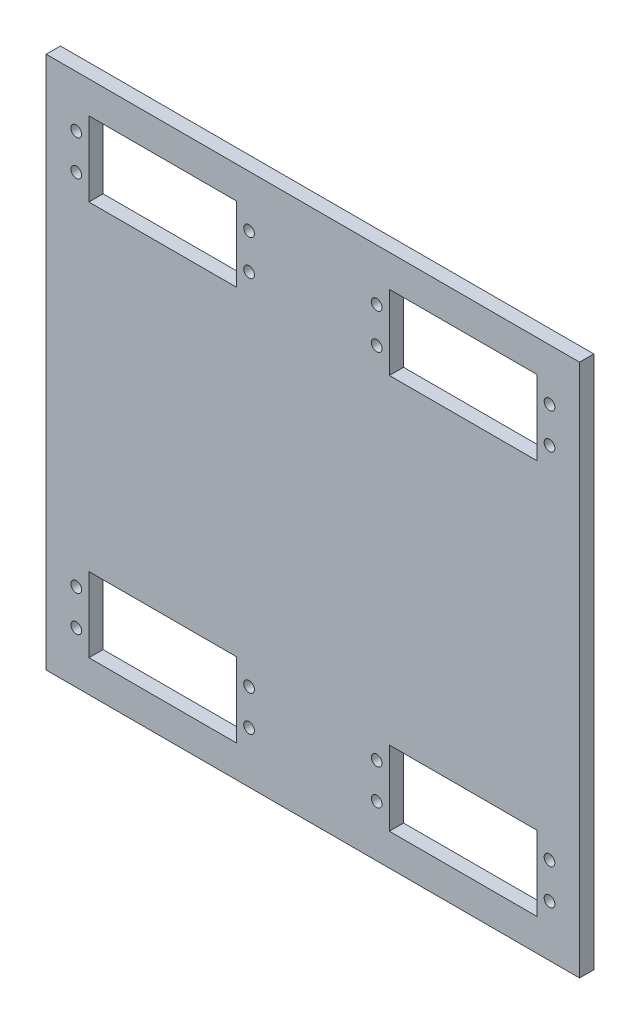
SolidWorks part; units mm, degrees
ref_plane "Plano frontal" through (0, 0, 0) normal (0, 0, 1) x (1, 0, 0)
ref_plane "Plano superior" through (0, 0, 0) normal (0, 1, 0) x (1, 0, 0)
ref_plane "Plano direito" through (0, 0, 0) normal (1, 0, 0) x (0, 0, -1)
sketch "Esboço1" plane through (0, 0, 0) normal (0, 0, 1) x (1, 0, 0)
  line L0 (66.55, 60.5) -> (66.55, 50.5) construction
  line L1 (-75, 75) -> (75, 75)
  line L2 (-75, 75) -> (-75, -75)
  line L3 (-75, -75) -> (75, -75)
  line L4 (75, 75) -> (75, -75)
  line L5 (-75, 75) -> (75, -75) construction
  line L6 (-75, -75) -> (75, 75) construction
  line L7 (-63, 66) -> (-21.5, 66)
  line L8 (-63, 66) -> (-63, 45)
  line L9 (-63, 45) -> (-21.5, 45)
  line L10 (-21.5, 66) -> (-21.5, 45)
  line L11 (69.6, 45) -> (63, 45) construction
  line L12 (69.6, 66) -> (69.6, 45) construction
  line L13 (63, 66) -> (69.6, 66) construction
  line L14 (14.9, 45) -> (21.5, 45) construction
  line L15 (14.9, 66) -> (14.9, 45) construction
  line L16 (21.5, 66) -> (14.9, 66) construction
  line L17 (21.5, 66) -> (21.5, 45)
  line L18 (63, 45) -> (21.5, 45)
  line L19 (63, 66) -> (63, 45)
  line L20 (63, 66) -> (21.5, 66)
  line L21 (-66.55, -60.5) -> (-66.55, -50.5) construction
  line L22 (-69.6, -45) -> (-63, -45) construction
  line L23 (-69.6, -66) -> (-69.6, -45) construction
  line L24 (-63, -66) -> (-69.6, -66) construction
  line L25 (-14.9, -45) -> (-21.5, -45) construction
  line L26 (-14.9, -66) -> (-14.9, -45) construction
  line L27 (-21.5, -66) -> (-14.9, -66) construction
  line L28 (-42.25, 66) -> (-42.25, 75) construction
  line L29 (-63, 55.5) -> (-75, 55.5) construction
  line L30 (-21.5, 66) -> (-14.9, 66) construction
  line L31 (-14.9, 66) -> (-14.9, 45) construction
  line L32 (-14.9, 45) -> (-21.5, 45) construction
  line L33 (-63, 66) -> (-69.6, 66) construction
  line L34 (-69.6, 66) -> (-69.6, 45) construction
  line L35 (-69.6, 45) -> (-63, 45) construction
  line L36 (21.5, -66) -> (14.9, -66) construction
  line L37 (14.9, -66) -> (14.9, -45) construction
  line L38 (14.9, -45) -> (21.5, -45) construction
  line L39 (-66.55, 60.5) -> (-66.55, 50.5) construction
  line L40 (0, 75) -> (0, 0) construction
  line L41 (0, 0) -> (-75, 0) construction
  line L42 (63, -66) -> (69.6, -66) construction
  line L43 (69.6, -66) -> (69.6, -45) construction
  line L44 (69.6, -45) -> (63, -45) construction
  line L45 (66.55, -60.5) -> (66.55, -50.5) construction
  line L46 (63, -66) -> (21.5, -66)
  line L47 (63, -66) -> (63, -45)
  line L48 (63, -45) -> (21.5, -45)
  line L49 (21.5, -66) -> (21.5, -45)
  line L50 (-21.5, -66) -> (-21.5, -45)
  line L51 (-63, -45) -> (-21.5, -45)
  line L52 (-63, -66) -> (-63, -45)
  line L53 (-63, -66) -> (-21.5, -66)
  circle A0 centre (-66.55, 60.5) radius 1.5
  circle A1 centre (-66.55, 50.5) radius 1.5
  circle A2 centre (-17.95, 60.5) radius 1.5
  circle A3 centre (-17.95, 50.5) radius 1.5
  circle A4 centre (17.95, 50.5) radius 1.5
  circle A5 centre (17.95, 60.5) radius 1.5
  circle A6 centre (66.55, 50.5) radius 1.5
  circle A7 centre (66.55, 60.5) radius 1.5
  circle A8 centre (66.55, -60.5) radius 1.5
  circle A9 centre (66.55, -50.5) radius 1.5
  circle A10 centre (17.95, -60.5) radius 1.5
  circle A11 centre (17.95, -50.5) radius 1.5
  circle A12 centre (-17.95, -50.5) radius 1.5
  circle A13 centre (-17.95, -60.5) radius 1.5
  circle A14 centre (-66.55, -50.5) radius 1.5
  circle A15 centre (-66.55, -60.5) radius 1.5
  point P0 (0, 0)
  point P48 (-66.55, 55.5)
  dimension "D8" = 3
  dimension "D1" = 41.5
  dimension "D2" = 21
  dimension "D3" = 12
  dimension "D4" = 9
  dimension "D5" = 150
  dimension "D6" = 150
  dimension "D7" = 6.6
  dimension "D9" = 10
  dimension "D10" = 48.6
extrude "Ressalto-extrusão1" add sketch "Esboço1" along normal blind 4
